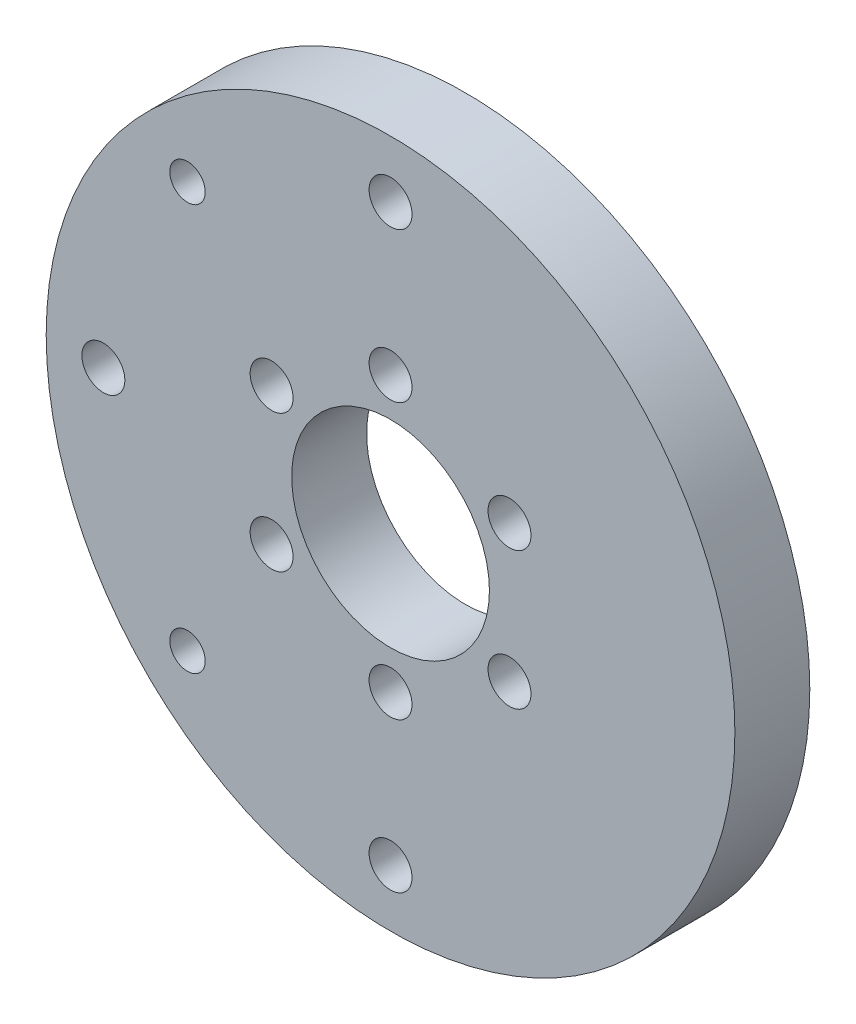
SolidWorks part; units mm, degrees
material "Balsa"
ref_plane "Front Plane" through (0, 0, 0) normal (0, 0, 1) x (1, 0, 0)
ref_plane "Top Plane" through (0, 0, 0) normal (0, 1, 0) x (1, 0, 0)
ref_plane "Right Plane" through (0, 0, 0) normal (1, 0, 0) x (0, 0, -1)
sketch "Sketch1" plane through (0, 0, 0) normal (0, 0, 1) x (1, 0, 0)
  circle A0 centre (0, 0) radius 27.5
  circle A1 centre (0, 0) radius 8
  circle A2 centre (0, 0) radius 23 construction
  circle A3 centre (0, 23) radius 1.8
  circle A4 centre (16.2635, 16.2635) radius 1.5 construction
  circle A5 centre (23, 0) radius 1.8 construction
  circle A6 centre (16.2635, -16.2635) radius 1.5 construction
  circle A7 centre (0, -23) radius 1.8
  circle A8 centre (-16.2635, -16.2635) radius 1.5
  circle A9 centre (-23, 0) radius 1.8
  circle A10 centre (-16.2635, 16.2635) radius 1.5
  circle A11 centre (0, 0) radius 11 construction
  circle A12 centre (0, 11) radius 1.8
  circle A13 centre (9.5263, 5.5) radius 1.8
  circle A14 centre (9.5263, -5.5) radius 1.8
  circle A15 centre (0, -11) radius 1.8
  circle A16 centre (-9.5263, -5.5) radius 1.8
  circle A17 centre (-9.5263, 5.5) radius 1.8
  dimension "D1" = 55
  dimension "D2" = 16
  dimension "D4" = 46
  dimension "D5" = 3.6
  dimension "D6" = 3
  dimension "D8" = 3.6
  dimension "D10" = 22
  dimension "D3" = 45
  dimension "D9" = 60
  dimension "D7" = 4
  dimension "D11" = 3
extrude "Boss-Extrude1" add sketch "Sketch1" along normal blind 6
other "Move Face1" face at (-14.7635, -16.2635, 6) face at (-21.2, 0, 6) face at (-14.7635, 16.2635, 6) face at (1.8, 23, 6) face at (27.5, 0, 6) face at (8, 0, 6) face at (1.8, 11, 6) face at (1.8, -23, 6) face at (11.3263, 5.5, 6) face at (11.3263, -5.5, 6) face at (1.8, -11, 6) face at (-7.7263, -5.5, 6) face at (-7.7263, 5.5, 6) parameters "D1"=0.08
